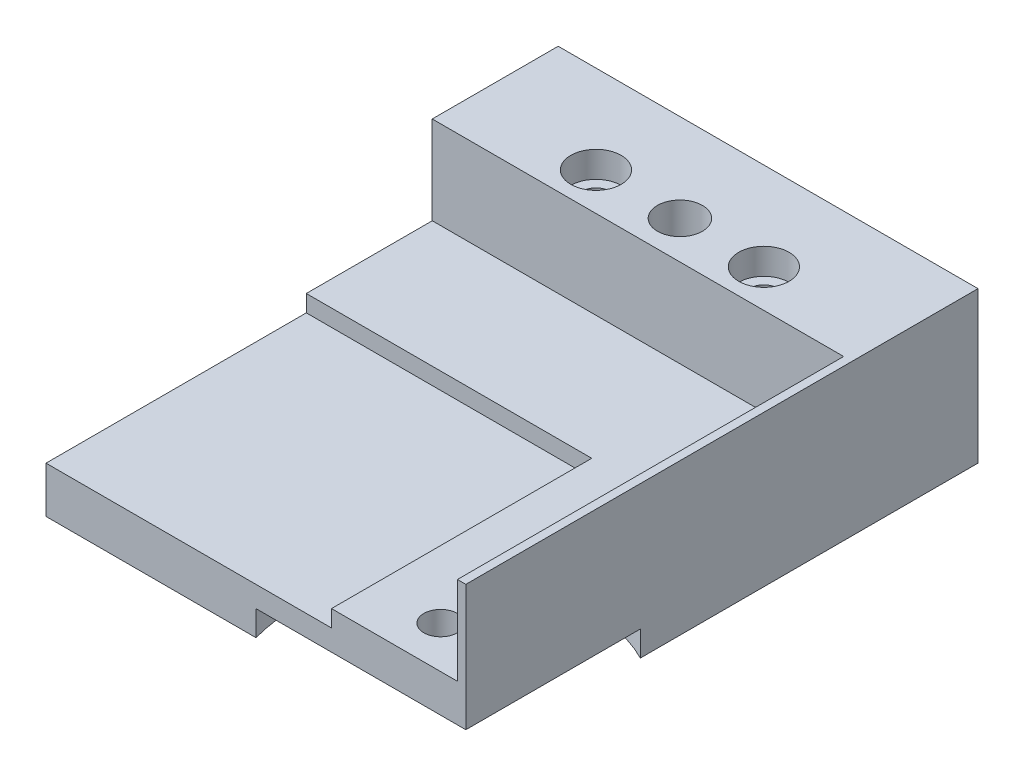
SolidWorks part; units mm, degrees
other "Markup1"
sketch "Sketch5" plane through (0, 18, 0) normal (-0.806, 0.0775, 0.5868) x (0.5918, 0.1268, 0.7961)
other "Markup2"
sketch "Sketch6" plane through (0, 18, 0) normal (-0.8829, 0.0686, 0.4646) x (0.4687, 0.0665, 0.8808)
ref_plane "Front Plane" through (0, 0, 0) normal (0, 0, 1) x (1, 0, 0)
ref_plane "Top Plane" through (0, 0, 0) normal (0, 1, 0) x (1, 0, 0)
ref_plane "Right Plane" through (0, 0, 0) normal (1, 0, 0) x (0, 0, -1)
sketch "OutlineSketch2" plane through (0, 0, 0) normal (0, 1, 0) x (1, 0, 0)
  line L1 (0, 0) -> (50, 0)
  line L2 (0, 0) -> (0, 61)
  line L3 (0, 61) -> (50, 61)
  line L4 (50, 0) -> (50, 61)
  circle A0 centre (42, 5) radius 2
  dimension "D5" = 4
  dimension "D1" = 5
  dimension "D2" = 8
  dimension "D3" = 56
  dimension "D4" = 50
extrude "OutlineBoss-Extrude1" add sketch "OutlineSketch2" along normal blind 18
sketch "BuildPlateCutoutSketch1" plane through (0, 18, 0) normal (0, 1, 0) x (1, 0, 0)
  line L1 (0, 0) -> (49, 0)
  line L2 (0, 0) -> (0, 46)
  line L3 (0, 46) -> (49, 46)
  line L4 (49, 0) -> (49, 46)
  dimension "D1" = 7
  dimension "D2" = 41
extrude "BuildPlateCutoutCut-Extrude7" cut sketch "BuildPlateCutoutSketch1" against normal blind 10.5
sketch "HeatMatCutSketch3" plane through (0, 7.5, 0) normal (0, 1, 0) x (1, 0, 0)
  line L0 (0, 0) -> (49, 0) construction
  line L1 (0, 0) -> (34, 0)
  line L2 (0, 0) -> (0, 31)
  line L3 (0, 31) -> (34, 31)
  line L4 (34, 0) -> (34, 31)
  line L5 (0, 46) -> (0, 0) construction
  line L6 (49, 46) -> (0, 46) construction
  line L7 (49, 0) -> (49, 46) construction
  dimension "D1" = 15
  dimension "D2" = 15
extrude "HeatMatCut-Extrude8" cut sketch "HeatMatCutSketch3" against normal blind 2
sketch "BallJointCutoutSketch4" plane through (0, 0, 0) normal (0, -1, 0) x (1, 0, 0)
  line L0 (25.0209, 0) -> (50, 0)
  line L2 (50, 0) -> (50, -20.7889)
  line L4 (50, 0) -> (50, -61) construction
  arc A0 (25.0209, 0) -> (50, -20.7889) centre (42, -5) ccw
  dimension "D1" = 35.4
extrude "BallJointCut-Extrude9" cut sketch "BallJointCutoutSketch4" against normal blind 3
sketch "Sketch1" plane through (0, 18, 0) normal (0, 1, 0) x (1, 0, 0)
  line L0 (50, 0) -> (50, 61) construction
  line L2 (49, 46) -> (0, 46) construction
  circle A0 centre (35, 50.5) radius 1.75
  circle A1 centre (25, 50.5) radius 2.675
  circle A2 centre (15, 50.5) radius 1.75
  dimension "D1" = 3.5
  dimension "D2" = 5.35
  dimension "D3" = 20
  dimension "D4" = 10
  dimension "D5" = 25
  dimension "D6" = 4.5
extrude "ZEndStopSwitchMountHolesCut-Extrude1" cut sketch "Sketch1" against normal through all
sketch "Sketch3" plane through (0, 18, 0) normal (0, 1, 0) x (1, 0, 0)
  circle A0 centre (35, 50.5) radius 3
  circle A1 centre (15, 50.5) radius 3
  dimension "D1" = 6
extrude "ZEndStopSwitchMountBoreHolesCut-Extrude2" cut sketch "Sketch3" against normal blind 3.1
sketch "Sketch4" plane through (0, 0, 0) normal (0, -1, 0) x (1, 0, 0)
  circle A0 centre (25, -50.5) radius 4.125
  dimension "D1" = 8.25
extrude "ZEndStopSwitchConningTowertBoreCut-Extrude1" cut sketch "Sketch4" against normal blind 7.5
equation "\"BuildPlateStandoffHolesDistanceFromLeftOrRightSide\"= 7mm"
equation "\"BuildPlateStandoffHolesDistanceFromBackSide\"= 41mm"
equation "\"BedSpringHoleSize\"= \"M4HoleDiameter\""
equation "\"D5@OutlineSketch2\" = \"BedSpringHoleSize\""
equation "\"D1@OutlineBoss-Extrude1\" = \"BuildPlateZEndstopDepth\""
equation "\"BuildPlateStandoffHolesDistanceFromFront\"= 7mm"
equation "\"M4HoleDiameter\"= 4mm"
equation "\"D1@OutlineSketch2\"=\"RightedgeSize\"+ \"BedSpringHoleSize\""
equation "\"D2@OutlineSketch2\"=  \"BuildPlateStandoffHolesDistanceFromFront\" + \"RightedgeSize\""
equation "\"D3@OutlineSketch2\" = \"BuildPlateStandoffHolesDistanceFromBackSide\" + \"BackEdgeSize\""
equation "\"RightedgeSize\"= 1mm"
equation "\"MicroSwitchExtraMountingHeight\"= 2mm"
equation "\"ZEndStopSwitchDepth\"= 21mm"
equation "\"BuildPlateZEndstopDepth\"= \"ZEndStopSwitchConningTowerHeight\" + \"ZEndStopPlungerHeight\" - 1mm"
equation "\"BackEdgeSize\"= \"ZEndStopSwitchDepth\" - \"ZEndStopSwitchConningTowerDiameter\" + 2mm"
equation "\"M2HeatInsertHoleDiameter\"= 3mm'Spec"
equation "\"M2HeatInsertHoleDepth\"= 3.1mm'Spec"
equation "\"BuildPlateEndStopHolderWidth\"= 50mm"
equation "\"D4@OutlineSketch2\"=\"BuildPlateEndStopHolderWidth\""
equation "\"BuildPlateDepth\"= 8mm'Spec"
equation "\"D1@BuildPlateCutoutSketch1\" = \"BuildPlateStandoffHolesDistanceFromLeftOrRightSide\""
equation "\"D2@BuildPlateCutoutSketch1\" = \"BuildPlateStandoffHolesDistanceFromBackSide\""
equation "\"D1@BuildPlateCutoutCut-Extrude7\" = \"BuildPlateDepth\" + \"MagneticPlateDepth\""
equation "\"BallJointDiameter\"= 1in"
equation "\"HeatMatBuildPlateBorderSize\"=15"
equation "\"D1@HeatMatCutSketch3\"=\"HeatMatBuildPlateBorderSize\""
equation "\"D2@HeatMatCutSketch3\"=\"HeatMatBuildPlateBorderSize\""
equation "\"D1@BallJointCutoutSketch4\"=\"BallJointDiameter\" + 10mm"
equation "\"ZEndStopSwitchHeight\"= 8mm"
equation "\"D5@Sketch1\"=\"BuildPlateEndStopHolderWidth\" /2"
equation "\"ZEndStopDistanceBetweenMountingHoles\"=20"
equation "\"D3@Sketch1\"=\"ZEndStopDistanceBetweenMountingHoles\""
equation "\"D4@Sketch1\"=\"ZEndStopDistanceBetweenMountingHoles\"/2"
equation "\"ZEndStopSwitchConningTowerDiameter\"= 8mm"
equation "\"ZEndStopSwitchConningTowerHeight\"= 7mm"
equation "\"D6@Sketch1\"=\"ZEndStopSwitchPlungerDiameter\"/2 + 2mm"
equation "\"ZEndStopSwitchPlungerDiameter\"=5"
equation "\"D2@Sketch1\"=\"ZEndStopSwitchPlungerDiameter\" + .35mm"
equation "\"D1@Sketch4\"=\"ZEndStopSwitchConningTowerDiameter\" + .25mm"
equation "\"D1@ZEndStopSwitchConningTowertBoreCut-Extrude1\" = \"ZEndStopSwitchConningTowerHeight\" + .5mm"
equation "\"M3ButtonHeadHeight\"=3.1"
equation "\"D1@ZEndStopSwitchMountBoreHolesCut-Extrude2\"=\"M3ButtonHeadHeight\""
equation "\"ZEndStopPlungerHeight\"= 12mm"
equation "\"MagneticPlateDepth\"= 2.5mm"
